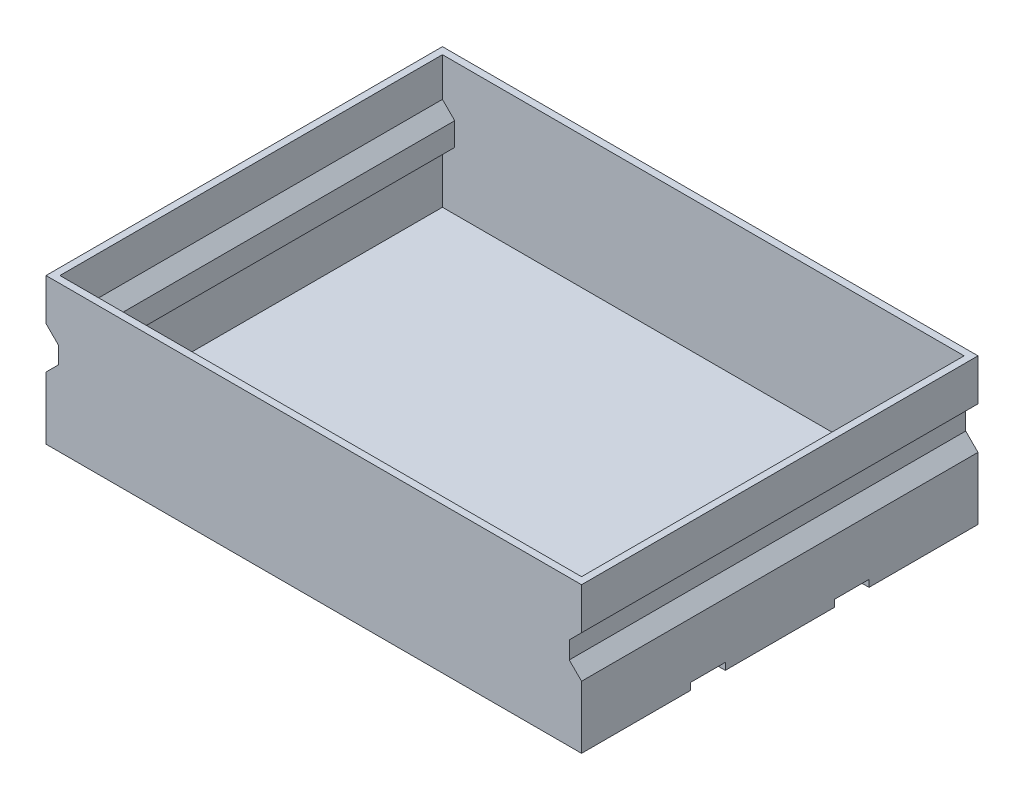
SolidWorks part; units mm, degrees
ref_plane "Front Plane" through (0, 0, 0) normal (0, 0, 1) x (1, 0, 0)
ref_plane "Top Plane" through (0, 0, 0) normal (0, 1, 0) x (1, 0, 0)
ref_plane "Right Plane" through (0, 0, 0) normal (1, 0, 0) x (0, 0, -1)
sketch "Sketch1" plane through (0, 0, 0) normal (0, 1, 0) x (1, 0, 0)
  line L0 (-75, 55) -> (75, -55)
  line L1 (-75, 55) -> (75, 55)
  line L2 (-75, 55) -> (-75, -55)
  line L3 (-75, -55) -> (75, -55)
  line L4 (75, 55) -> (75, -55)
  line L5 (-77, -57) -> (77, 57) construction
  line L6 (-77, 57) -> (77, 57)
  line L7 (-77, 57) -> (-77, -57)
  line L8 (-77, -57) -> (77, -57)
  line L9 (77, 57) -> (77, -57)
  line L10 (-75, 55) -> (-75, 57) construction
  line L11 (-75, 55) -> (-77, 55) construction
  dimension "D1" = 110
  dimension "D2" = 150
  dimension "D3" = 2
extrude "Boss-Extrude1" add sketch "Sketch1" against normal blind 2 contours L4 L1 L0 | L2 L3 L0 | L9 L6 L7 L8 L1 L4 L3 L2
sketch "Sketch2" plane through (0, 0, 0) normal (0, 0, 1) x (1, 0, 0)
  line L0 (-77, 0) -> (-77, 13.9645)
  line L1 (-77, 13.9645) -> (-73.4645, 17.5)
  line L2 (-73.4645, 17.5) -> (-73.4645, 22.5)
  line L3 (-73.4645, 22.5) -> (-77, 26.0355)
  line L4 (-77, 26.0355) -> (-77, 38)
  line L5 (-77, 38) -> (-75, 38)
  line L6 (-75, 38) -> (-75, 26.0355) construction
  line L7 (-75, 26.0355) -> (-71.4645, 22.5) construction
  line L8 (-71.4645, 22.5) -> (-71.4645, 17.5)
  line L9 (-71.4645, 17.5) -> (-75, 13.9645) construction
  line L10 (-75, 13.9645) -> (-75, 0) construction
  line L11 (-77, 0) -> (77, 0) construction
  line L12 (-75, 0) -> (-77, 0)
  line L13 (-75, 13.9645) -> (-77, 13.9645) construction
  line L14 (-71.4645, 17.5) -> (-73.4645, 17.5) construction
  line L15 (-71.4645, 22.5) -> (-73.4645, 22.5) construction
  line L16 (-75, 26.0355) -> (-77, 26.0355) construction
  line L17 (-71.4645, 17.5) -> (-71.4645, 16.6716)
  line L18 (-71.4645, 16.6716) -> (-75, 13.136)
  line L19 (-75.2322, 15.7322) -> (-73.818, 14.318) construction
  line L20 (-71.4645, 22.5) -> (-71.4645, 23.3284)
  line L21 (-71.4645, 23.3284) -> (-75, 26.864)
  line L22 (-75.2322, 24.2678) -> (-73.818, 25.682) construction
  line L23 (-77, -2) -> (77, -2) construction
  line L24 (-77, 26.0355) -> (-77, 13.9645) construction
  line L25 (-71.4645, 20) -> (-73.4645, 20) construction
  line L26 (0, 66.076) -> (0, 25.682) construction
  line L27 (71.4645, 20) -> (73.4645, 20) construction
  line L28 (77, 26.0355) -> (77, 13.9645) construction
  line L29 (75.2322, 24.2678) -> (73.818, 25.682) construction
  line L30 (75.2322, 15.7322) -> (73.818, 14.318) construction
  line L31 (75, 26.0355) -> (77, 26.0355) construction
  line L32 (71.4645, 22.5) -> (73.4645, 22.5) construction
  line L33 (71.4645, 17.5) -> (73.4645, 17.5) construction
  line L34 (75, 13.9645) -> (77, 13.9645) construction
  line L35 (75, 13.9645) -> (75, 0) construction
  line L36 (71.4645, 17.5) -> (75, 13.9645) construction
  line L37 (75, 26.0355) -> (71.4645, 22.5) construction
  line L38 (75, 38) -> (75, 26.0355) construction
  line L39 (75, 38) -> (75, 26.864)
  line L40 (75, 13.136) -> (75, 0)
  line L41 (71.4645, 23.3284) -> (75, 26.864)
  line L42 (71.4645, 22.5) -> (71.4645, 23.3284)
  line L43 (71.4645, 16.6716) -> (75, 13.136)
  line L44 (71.4645, 17.5) -> (71.4645, 16.6716)
  line L45 (75, 0) -> (77, 0)
  line L46 (71.4645, 22.5) -> (71.4645, 17.5)
  line L47 (77, 38) -> (75, 38)
  line L48 (77, 26.0355) -> (77, 38)
  line L49 (73.4645, 22.5) -> (77, 26.0355)
  line L50 (73.4645, 17.5) -> (73.4645, 22.5)
  line L51 (-75, 13.136) -> (-75, 0)
  line L52 (-75, 38) -> (-75, 26.864)
  line L53 (77, 13.9645) -> (73.4645, 17.5)
  line L54 (77, 0) -> (77, 13.9645)
  dimension "D1" = 2
  dimension "D2" = 135
  dimension "D3" = 135
  dimension "D4" = 40
  dimension "D5" = 5
  dimension "D6" = 5
  dimension "D7" = 5
  dimension "D8" = 20
extrude "Boss-Extrude2" add sketch "Sketch2" along normal up to surface and the other way up to surface up to face at (0, -1, 57) other way up to face at (0, -1, -57)
sketch "Sketch3" plane through (0, 0, -57) normal (0, 0, -1) x (-1, 0, 0)
  line L0 (-75, 38) -> (75, 38)
  line L1 (75, 38) -> (75, 26.864)
  line L2 (75, 26.864) -> (71.4645, 23.3284)
  line L3 (71.4645, 23.3284) -> (71.4645, 16.6716)
  line L4 (71.4645, 16.6716) -> (75, 13.136) construction
  line L5 (71.4645, 23.3284) -> (71.4645, 16.6716) construction
  line L6 (71.4645, 16.6716) -> (75, 13.136)
  line L7 (75, 13.136) -> (75, 0)
  line L8 (75, 0) -> (-75, 0)
  line L9 (-75, 0) -> (-75, 13.136)
  line L10 (-75, 13.136) -> (-71.4645, 16.6716)
  line L11 (-71.4645, 16.6716) -> (-71.4645, 23.3284)
  line L12 (-71.4645, 23.3284) -> (-75, 26.864)
  line L13 (-75, 26.864) -> (-75, 38)
extrude "Boss-Extrude3" add sketch "Sketch3" against normal blind 2
mirror "Mirror1" about plane through (0, 0, 0) normal (0, 0, 1) of "Boss-Extrude3"
sketch "Sketch4" plane through (0, -2, 0) normal (0, -1, 0) x (1, 0, 0)
  line L0 (77, -57) -> (77, 57) construction
  line L1 (-77, -57) -> (77, -57)
  line L2 (-77, -57) -> (-77, -25.6667)
  line L3 (-77, -25.6667) -> (77, -25.6667)
  line L4 (77, -57) -> (77, -25.6667)
  line L5 (-77, -57) -> (-77, 57) construction
  line L6 (-77, -15.6667) -> (77, -15.6667)
  line L7 (-77, -15.6667) -> (-77, 15.6667)
  line L8 (-77, 15.6667) -> (77, 15.6667)
  line L9 (77, -15.6667) -> (77, 15.6667)
  line L10 (-77, -15.6667) -> (77, 15.6667) construction
  line L11 (-77, 25.6667) -> (77, 25.6667)
  line L12 (-77, 25.6667) -> (-77, 57)
  line L13 (-77, 57) -> (77, 57)
  line L14 (77, 25.6667) -> (77, 57)
  line L15 (0, -25.6667) -> (0, -15.6667) construction
  line L16 (0, 25.6667) -> (0, 15.6667) construction
  point P38 (-25.6667, 0)
  dimension "D1" = 10
extrude "Boss-Extrude4" add sketch "Sketch4" along normal blind 2
